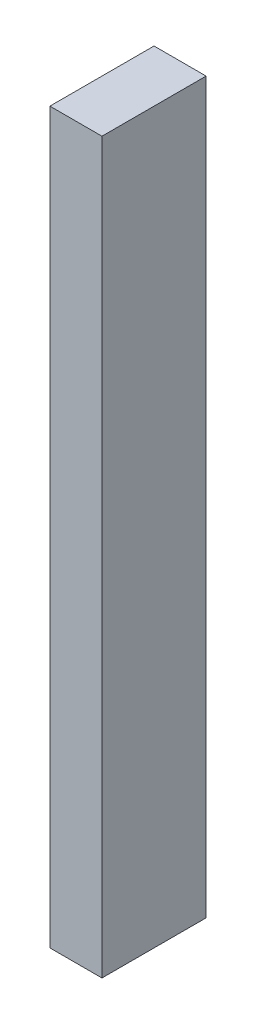
SolidWorks part; units mm, degrees
ref_plane "Front Plane" through (0, 0, 0) normal (0, 0, 1) x (1, 0, 0)
ref_plane "Top Plane" through (0, 0, 0) normal (0, 1, 0) x (1, 0, 0)
ref_plane "Right Plane" through (0, 0, 0) normal (1, 0, 0) x (0, 0, -1)
sketch "Sketch1" plane through (0, 0, 0) normal (0, 0, 1) x (1, 0, 0)
  line L0 (-254, 133.35) -> (-254, 12.7) construction
  line L1 (-273.05, 133.35) -> (-254, 133.35)
  line L2 (-273.05, 133.35) -> (-273.05, -133.35)
  line L3 (-273.05, -133.35) -> (-254, -133.35)
  line L4 (-254, 133.35) -> (-254, -133.35)
  line L5 (273.05, -133.35) -> (-273.05, -133.35) construction
extrude "Boss-Extrude1" add sketch "Sketch1" along normal blind 38.1
